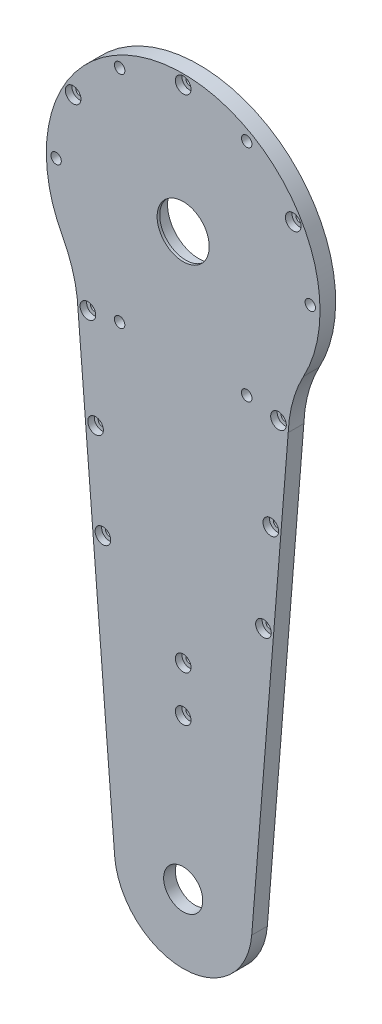
SolidWorks part; units mm, degrees
ref_plane "Front Plane" through (0, 0, 0) normal (0, 0, 1) x (1, 0, 0)
ref_plane "Top Plane" through (0, 0, 0) normal (0, 1, 0) x (1, 0, 0)
ref_plane "Right Plane" through (0, 0, 0) normal (1, 0, 0) x (0, 0, -1)
sketch "Sketch2" plane through (0, 0, 0) normal (0, 0, 1) x (1, 0, 0)
  line L13 (26.292, -220.6068) -> (40.2989, -46.6068)
  line L14 (-40.2989, -46.6068) -> (-26.292, -220.6068)
  circle A0 centre (36.5609, -44.5041) radius 1.5
  circle A1 centre (0, -218.5) radius 7.5
  circle A2 centre (33.6152, -81.2662) radius 1.5
  circle A3 centre (30.7985, -116.4179) radius 1.5
  circle A4 centre (0, -143.3084) radius 1.5
  circle A5 centre (0, -160.8084) radius 1.5
  circle A6 centre (-30.7985, -116.4179) radius 1.5
  circle A7 centre (-33.6152, -81.2662) radius 1.5
  circle A8 centre (-36.5609, -44.5041) radius 1.5
  arc A9 (46.1688, -24.9938) -> (-46.1688, -24.9938) centre (0, 0) ccw
  arc A18 (-6.4975, 52.0964) -> (-46.1688, -24.9938) centre (0, 0) ccw
  arc A23 (46.1688, -24.9938) -> (6.4975, 52.0964) centre (0, 0) ccw
  arc A24 (46.1688, -24.9938) -> (40.2989, -46.6068) centre (90.2603, -48.5723) ccw
  arc A25 (-26.292, -220.6068) -> (26.292, -220.6068) centre (0, -218.5) ccw
  arc A26 (-40.2989, -46.6068) -> (-46.1688, -24.9938) centre (-90.2603, -48.5723) ccw
  circle A29 centre (0, 0) radius 12
  circle A30 centre (36.5609, -44.5041) radius 2.05
  circle A31 centre (33.6152, -81.2662) radius 2.05
  circle A32 centre (-36.5609, -44.5041) radius 2.05
  circle A33 centre (-33.6152, -81.2662) radius 2.05
  circle A34 centre (-30.7985, -116.4179) radius 2.05
  circle A35 centre (30.7985, -116.4179) radius 2.05
  circle A36 centre (0, -160.8084) radius 2.05
  circle A37 centre (0, -143.3084) radius 2.05
  dimension "D1" = 15
  dimension "D2" = 26.3763
  dimension "D5" = 24
  dimension "D6" = 105
  dimension "D7" = 4.1
  dimension "D8" = 3
  dimension "D9" = 3
  dimension "D10" = 3
  dimension "D11" = 3
  dimension "D12" = 3
  dimension "D13" = 3
  dimension "D14" = 3
  dimension "D15" = 3
  dimension "D3" = 174
  dimension "D4" = 174
  dimension "D16" = 218.5
extrude "Boss-Extrude1" add sketch "Sketch2" along normal blind 6 contours A26 L14 A25 L13 A24 A9 A37 A36 A35 A34 A33 A32 A31 A30 A29 A1 | A35 A3 | A31 A2 | A30 A0 | A32 A8 | A33 A7 | A34 A6 | A37 A4 | A36 A5
sketch "Sketch3" plane through (0, 0, 6) normal (0, 0, 1) x (1, 0, 0)
  circle A0 centre (0, 0) radius 10
  dimension "D1" = 20
extrude "Extrude-Thin1" add sketch "Sketch3" against normal blind 1 thin
sketch "Sketch4" plane through (0, 0, 0) normal (0, 0, -1) x (-1, 0, 0)
  circle A0 centre (0, 0) radius 48.75 construction
  circle A1 centre (-48.75, 0) radius 2
  circle A2 centre (-24.375, 42.2187) radius 2
  circle A3 centre (24.375, 42.2187) radius 2
  circle A4 centre (48.75, 0) radius 2
  circle A5 centre (24.375, -42.2187) radius 2
  circle A6 centre (-24.375, -42.2187) radius 2
  point P17 (0, 0)
  dimension "D1" = 97.5
  dimension "D2" = 4
  dimension "D3" = 6
extrude "Cut-Extrude1" cut sketch "Sketch4" against normal blind 10
sketch "Sketch5" plane through (0, 0, 6) normal (0, 0, 1) x (1, 0, 0)
  circle A0 centre (36.5609, -44.5041) radius 1.5 construction
  circle A1 centre (30.7985, -116.4179) radius 1.5 construction
  circle A2 centre (33.6152, -81.2662) radius 1.5 construction
  circle A3 centre (0, -160.8084) radius 1.5 construction
  circle A4 centre (0, -143.3084) radius 1.5 construction
  circle A5 centre (-30.7985, -116.4179) radius 1.5 construction
  circle A6 centre (-33.6152, -81.2662) radius 1.5 construction
  circle A7 centre (-36.5609, -44.5041) radius 1.5 construction
  circle A8 centre (36.5609, -44.5041) radius 1.5
  circle A9 centre (30.7985, -116.4179) radius 1.5
  circle A10 centre (33.6152, -81.2662) radius 1.5
  circle A11 centre (0, -160.8084) radius 1.5
  circle A12 centre (0, -143.3084) radius 1.5
  circle A13 centre (-30.7985, -116.4179) radius 1.5
  circle A14 centre (-33.6152, -81.2662) radius 1.5
  circle A15 centre (-36.5609, -44.5041) radius 1.5
extrude "Cut-Extrude-Thin1" cut sketch "Sketch5" against normal blind 2.5 thin
sketch "Sketch7" plane through (0, 0, 0) normal (0, 0, -1) x (-1, 0, 0)
  circle A0 centre (0, -218.5) radius 14
  dimension "D1" = 28
extrude "Cut-Extrude2" cut sketch "Sketch7" against normal blind 1.5
sketch "Sketch8" plane through (0, 0, 6) normal (0, 0, 1) x (1, 0, 0)
  circle A0 centre (0, 0) radius 48.75 construction
  circle A1 centre (0, 48.75) radius 1.5
  circle A2 centre (42.2187, 24.375) radius 1.5
  circle A3 centre (42.2187, -24.375) radius 1.5 [skipped]
  circle A4 centre (0, -48.75) radius 1.5 [skipped]
  circle A5 centre (-42.2187, -24.375) radius 1.5 [skipped]
  circle A6 centre (-42.2187, 24.375) radius 1.5
  point P19 (0, 0)
  dimension "D1" = 3
  dimension "D2" = 6
extrude "Cut-Extrude3" cut sketch "Sketch8" against normal up to surface (6 mm away) up to face at (-14, -218.5, 0)
sketch "Sketch9" plane through (0, 0, 6) normal (0, 0, 1) x (1, 0, 0)
  circle A0 centre (42.2187, 24.375) radius 1.5 construction
  circle A1 centre (-42.2187, 24.375) radius 1.5 construction
  circle A2 centre (0, 48.75) radius 1.5 construction
  circle A3 centre (42.2187, 24.375) radius 1.5 construction
  circle A4 centre (-42.2187, 24.375) radius 1.5 construction
  circle A5 centre (0, 48.75) radius 1.5 construction
  circle A6 centre (-42.2187, 24.375) radius 3
  circle A7 centre (0, 48.75) radius 3
  circle A8 centre (42.2187, 24.375) radius 3
  dimension "D1" = 6
  dimension "D2" = 6
  dimension "D3" = 6
extrude "Cut-Extrude4" cut sketch "Sketch9" against normal blind 2.5
